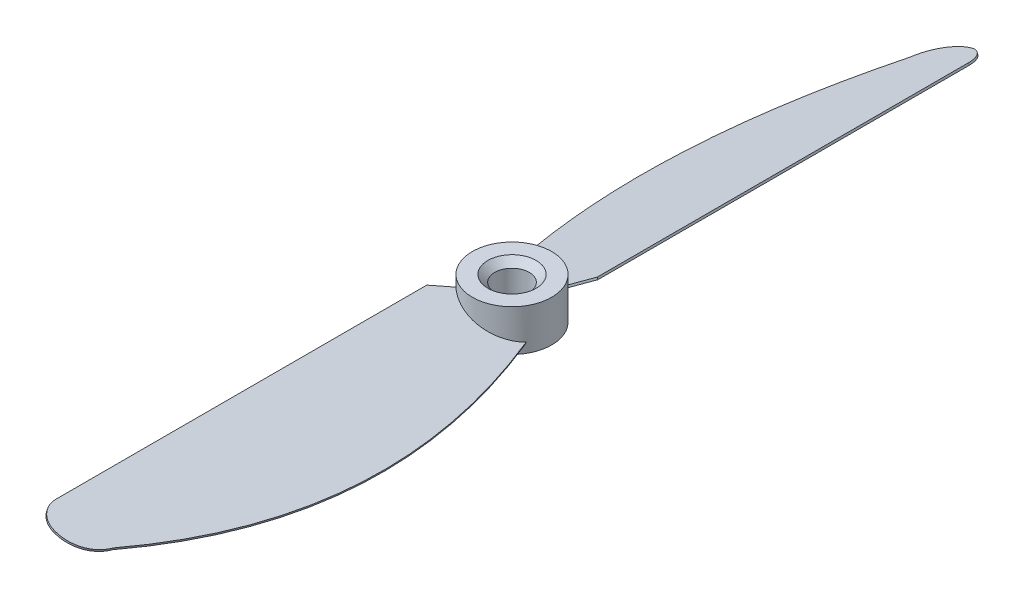
SolidWorks part; units mm, degrees
ref_plane "Front Plane" through (0, 0, 0) normal (0, 0, 1) x (1, 0, 0)
ref_plane "Top Plane" through (0, 0, 0) normal (0, 1, 0) x (1, 0, 0)
ref_plane "Right Plane" through (0, 0, 0) normal (1, 0, 0) x (0, 0, -1)
sketch "Sketch1" plane through (0, 0, 0) normal (0, 1, 0) x (1, 0, 0)
  circle A0 centre (0, 0) radius 5.75
  dimension "D1" = 11.5
extrude "Boss-Extrude1" add sketch "Sketch1" along normal mid plane 6
sketch "Sketch2" plane through (0, 0, 0) normal (0, 0, 1) x (1, 0, 0)
  line L0 (-5.75, 2.0233) -> (5.75, -2.0233) construction
  line L1 (-5.75, 3) -> (-5.75, -3) construction
  line L2 (5.75, -3) -> (5.75, 3) construction
  line L3 (-5.75, -3) -> (5.75, -3) construction
  dimension "D1" = 19.386
ref_plane "Plane1" through (0, 0, 0) normal (-0.3319, -0.9433, 0) x (0.9433, -0.3319, 0)
sketch "Sketch3" plane through (0, 0, 0) normal (-0.3319, -0.9433, 0) x (0.9433, -0.3319, 0)
  line L0 (-3.4854, 3.2396) -> (-6.0698, 6.6807)
  line L1 (-6.0698, 6.6807) -> (-6.0698, 60.5)
  line L2 (-3.0698, 63.5) -> (-2.8546, 63.5)
  arc A0 (1.9948, 59.7178) -> (-2.8546, 63.5) centre (-2.8546, 58.5) ccw
  arc A1 (-6.0698, 60.5) -> (-3.0698, 63.5) centre (-3.0698, 60.5) cw
  spline S0 degree 2 poles (-3.4854, 3.2396) (0.9163, 7.754) (4.813, 1.8488) knots 0 0 0 1 1 1
  spline S1 degree 2 poles (1.9948, 59.7178) (15.8597, 31.6128) (4.813, 1.8488) knots 0 0 0 1 1 1
  dimension "D3" = 5
  dimension "D4" = 3
extrude "Boss-Extrude2" add sketch "Sketch3" along normal mid plane 0.3
pattern_circular "CirPattern1" count 2 over 360 about axis through (0, 3, 0) along (0, -1, 0) of "Boss-Extrude2"
sketch "Sketch4" plane through (0, 3, 0) normal (0, 1, 0) x (1, 0, 0)
  circle A0 centre (0, 0) radius 2.5
  dimension "D1" = 5
extrude "Cut-Extrude1" cut sketch "Sketch4" against normal through all
chamfer "Chamfer1" distance 1 angle 45 2 edges at (0, -3, 2.5) (0, 3, 2.5)
